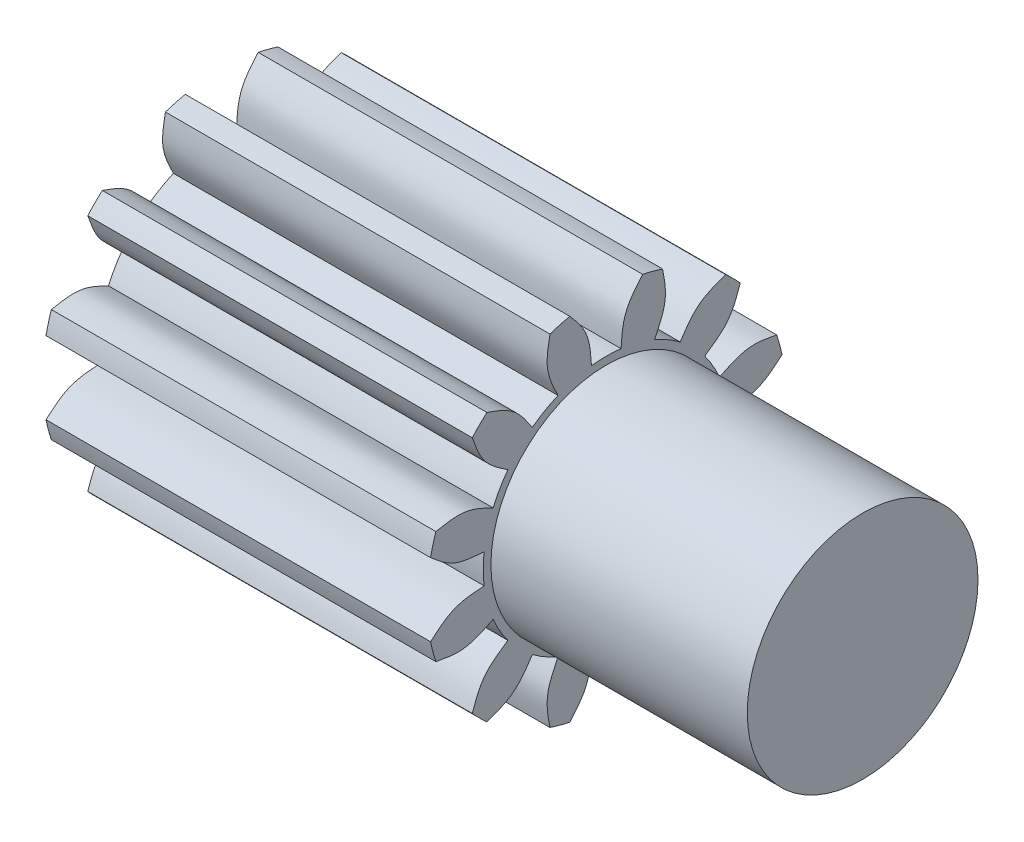
SolidWorks part; units mm, degrees
ref_plane "Front" through (0, 0, 0) normal (0, 0, 1) x (1, 0, 0)
ref_plane "Top" through (0, 0, 0) normal (0, 1, 0) x (1, 0, 0)
ref_plane "Right" through (0, 0, 0) normal (1, 0, 0) x (0, 0, -1)
sketch "Ritning 1" plane through (0, 0, 0) normal (0, 0, 1) x (1, 0, 0)
  line L0 (12.5, 1) -> (2.5, 1)
  line L1 (2.5, 1) -> (2.5, 3.5)
  line L2 (2.5, 3.5) -> (-12.5, 3.5)
  line L3 (12.5, 1) -> (12.5, -3.5)
  line L4 (-12.5, 3.5) -> (-12.5, -3.5)
  line L5 (-12.5, -3.5) -> (12.5, -3.5)
  dimension "D1" = 2.5
  dimension "D2" = 12.5
  dimension "D3" = 12.5
  dimension "D4" = 1
  dimension "D5" = 3.5
  dimension "D6" = 3.5
revolve "Kugghjulsämne" add sketch "Ritning 1" angle 360 about L5
sketch "Ritning 2" plane through (-12.5, 0, 0) normal (-1, 0, 0) x (0, 0, 1)
  line L0 (0, -3.5) -> (0, 3.5) construction
  line L1 (1.4199, 3.3545) -> (0, 4.7744)
  line L2 (-1.4199, 3.3545) -> (0, 4.7744)
  line L3 (0, -3.5) -> (1.4199, -3.5) construction
  arc A0 (0.5768, 1.2652) -> (-0.5768, 1.2652) centre (0, -3.5) ccw
  circle A1 centre (0, -3.5) radius 7 construction
  spline S0 degree 3 poles (1.4199, 3.3545) (1.173, 3.0671) (0.6581, 2.4675) (0.6046, 1.6769) (0.5768, 1.2652) knots 0 0 0 0 0.479362 1 1 1 1
  spline S1 degree 3 poles (-1.4199, 3.3545) (-1.173, 3.0671) (-0.6581, 2.4675) (-0.6046, 1.6769) (-0.5768, 1.2652) knots 0 0 0 0 0.479362 1 1 1 1
  dimension "D1" = 4.8
  dimension "D2" = 0.5768
  dimension "D3" = 0.7854
  dimension "D4" = 1.4199
  dimension "D5" = 5.9484
  dimension "D6" = 0.7854
  dimension "D7" = 6.8545
extrude "Kugglucka" cut sketch "Ritning 2" against normal up to surface (15 mm away) up to face at (2.5, -3.5, 7)
pattern_circular "CirPattern" count 12 over 360 about axis through (-12.5, -3.5, 0) along (-1, 0, 0) of "Kugglucka"
